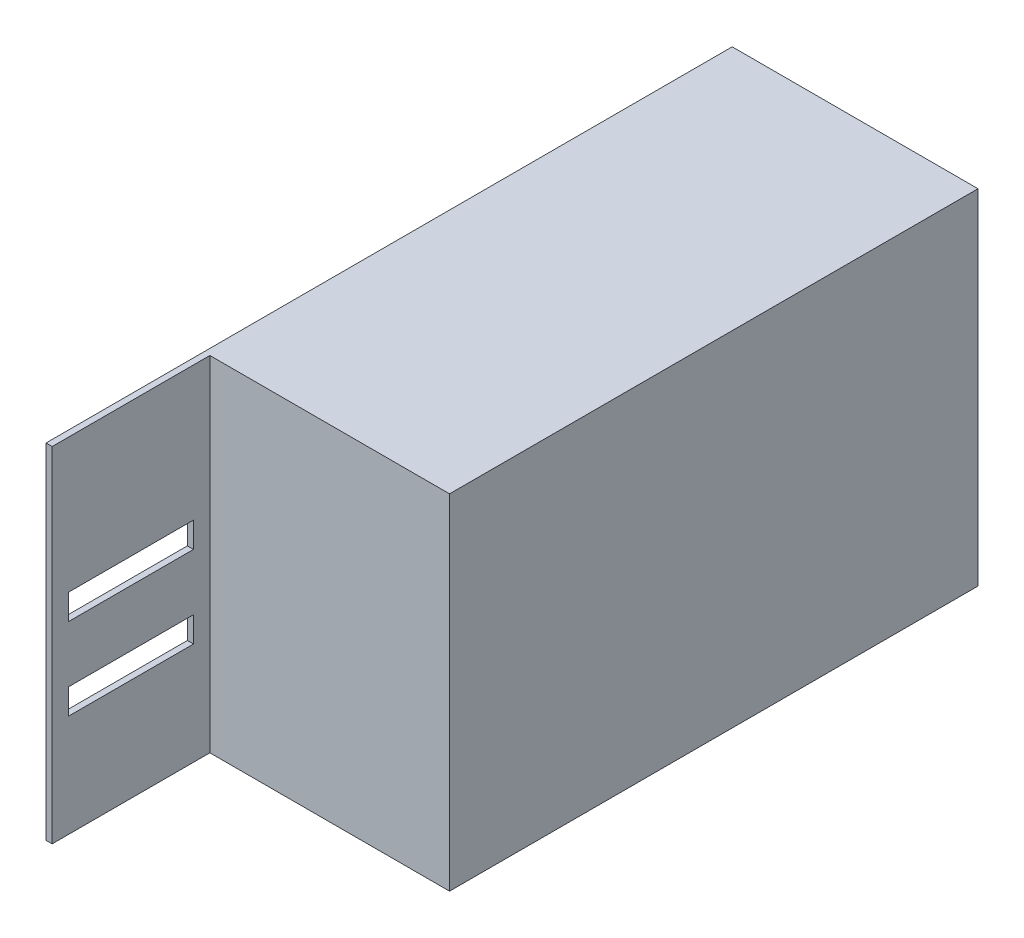
SolidWorks part; units mm, degrees
ref_plane "Front Plane" through (0, 0, 0) normal (1, 0, 0) x (0, 1, 0)
ref_plane "Top Plane" through (0, 0, 0) normal (0, 0, 1) x (0, 1, 0)
ref_plane "Right Plane" through (0, 0, 0) normal (0, 1, 0) x (-1, 0, 0)
sketch "Sketch1" plane through (0, 0, 0) normal (1, 0, 0) x (0, 1, 0)
  line L1 (0, 0) -> (84, 0)
  line L2 (0, 0) -> (0, -129)
  line L3 (0, -129) -> (84, -129)
  line L4 (84, 0) -> (84, -129)
  dimension "D1" = 129
  dimension "D2" = 84
extrude "Boss-Extrude1" add sketch "Sketch1" along normal blind 60
shell "Shell1" thickness 1.5
sketch "Sketch2" plane through (0, 0, -129) normal (0, 0, -1) x (1, 0, 0)
  line L1 (0, 0) -> (60, 0)
  line L2 (0, 0) -> (0, -84)
  line L3 (0, -84) -> (60, -84)
  line L4 (60, 0) -> (60, -84)
  line L5 (1.5, -82.5) -> (58.5, -82.5)
  line L6 (58.5, -1.5) -> (58.5, -82.5)
  line L7 (1.5, -1.5) -> (58.5, -1.5)
  line L8 (1.5, -1.5) -> (0, -1.5)
  line L9 (0, -1.5) -> (0, -82.5)
  line L10 (0, -82.5) -> (1.5, -82.5)
  line L12 (1.5, -1.5) -> (1.5, -82.5) construction
  dimension "D1" = 1.5
extrude "Cut-Extrude1" cut sketch "Sketch2" against normal up to surface (127.5 mm away) contours L7 L6 L5 L10 L9 L8 up to face at (29.25, 42, -1.5)
sketch "Sketch3" plane through (0, 0, 0) normal (-1, 0, 0) x (0, 0, 1)
  line L0 (-129, 84) -> (0, 84) construction
  line L1 (-1.5, 84) -> (38.5, 84)
  line L2 (-1.5, 84) -> (-1.5, 0)
  line L3 (-1.5, 0) -> (38.5, 0)
  line L4 (38.5, 84) -> (38.5, 0)
  line L5 (-1.5, 82.5) -> (-1.5, 1.5) construction
  line L6 (0, 0) -> (-129, 0) construction
  point P10 (-1.5, 42)
  dimension "D1" = 40
extrude "Boss-Extrude2" add sketch "Sketch3" against normal blind 1.5
sketch "Sketch4" plane through (1.5, 0, 0) normal (1, 0, 0) x (0, 0, -1)
  line L0 (-34.5, 0) -> (-34.5, 84) construction
  line L1 (-34.5, 25) -> (-4, 25)
  line L2 (-34.5, 25) -> (-34.5, 31.2)
  line L3 (-34.5, 31.2) -> (-4, 31.2)
  line L4 (-4, 25) -> (-4, 31.2)
  line L5 (-34.5, 45) -> (-4, 45)
  line L6 (-34.5, 45) -> (-34.5, 51.2)
  line L7 (-34.5, 51.2) -> (-4, 51.2)
  line L8 (-4, 45) -> (-4, 51.2)
  line L9 (0, 0) -> (-38.5, 0) construction
  line L10 (-38.5, 84) -> (0, 84) construction
  line L11 (-4, 0) -> (-4, 84) construction
  line L12 (-38.5, 0) -> (-38.5, 84) construction
  line L13 (0, 84) -> (0, 0) construction
  dimension "D1" = 6.2
  dimension "D2" = 6.2
  dimension "D3" = 13.8
  dimension "D4" = 25
  dimension "D5" = 4
  dimension "D6" = 4
extrude "Cut-Extrude2" cut sketch "Sketch4" against normal through all
